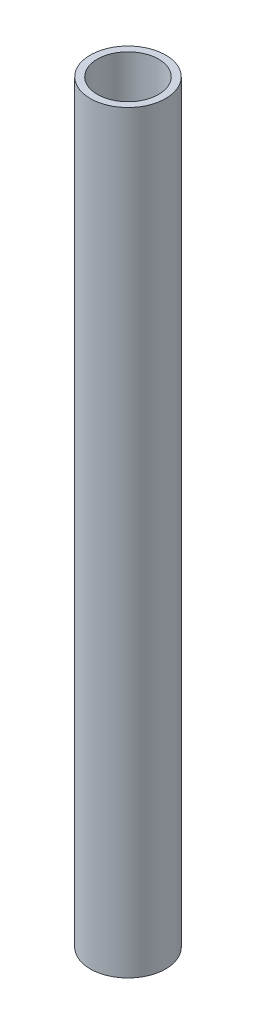
SolidWorks part; units mm, degrees
material "Thornel Mat VMA"
ref_plane "Front Plane" through (0, 0, 0) normal (0, 0, 1) x (1, 0, 0)
ref_plane "Top Plane" through (0, 0, 0) normal (0, 1, 0) x (1, 0, 0)
ref_plane "Right Plane" through (0, 0, 0) normal (1, 0, 0) x (0, 0, -1)
sketch "Sketch1" plane through (0, 0, 0) normal (0, 1, 0) x (1, 0, 0)
  circle A0 centre (0, 0) radius 6.5
  circle A1 centre (0, 0) radius 8
  dimension "D1" = 16
  dimension "D2" = 1.5
extrude "Boss-Extrude1" add sketch "Sketch1" along normal blind 160
